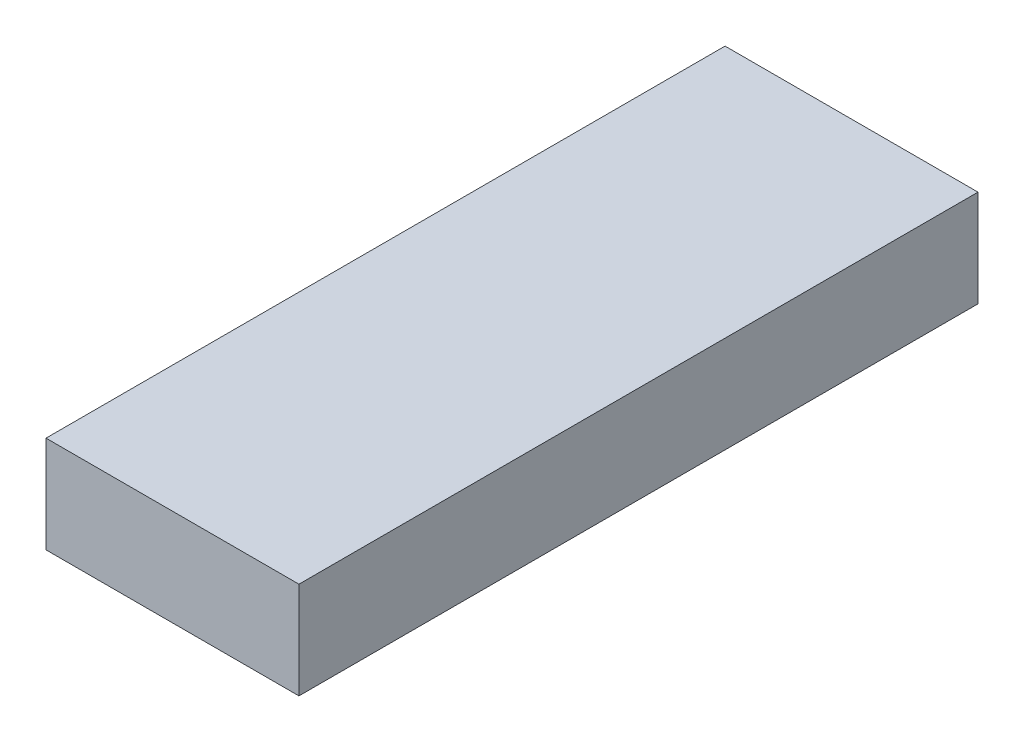
SolidWorks part; units mm, degrees
material "Cast Alloy Steel"
ref_plane "Front Plane" through (0, 0, 0) normal (0, 0, 1) x (1, 0, 0)
ref_plane "Top Plane" through (0, 0, 0) normal (0, 1, 0) x (1, 0, 0)
ref_plane "Right Plane" through (0, 0, 0) normal (1, 0, 0) x (0, 0, -1)
sketch "Sketch1" plane through (0, 0, 0) normal (0, 1, 0) x (1, 0, 0)
  line L1 (-36.9638, 19.5877) -> (0.8822, 19.5877)
  line L2 (-36.9638, 19.5877) -> (-36.9638, -82.0123)
  line L3 (-36.9638, -82.0123) -> (0.8822, -82.0123)
  line L4 (0.8822, 19.5877) -> (0.8822, -82.0123)
  dimension "D1" = 37.846
  dimension "D2" = 101.6
extrude "Extrude1" add sketch "Sketch1" along normal blind 14.478
